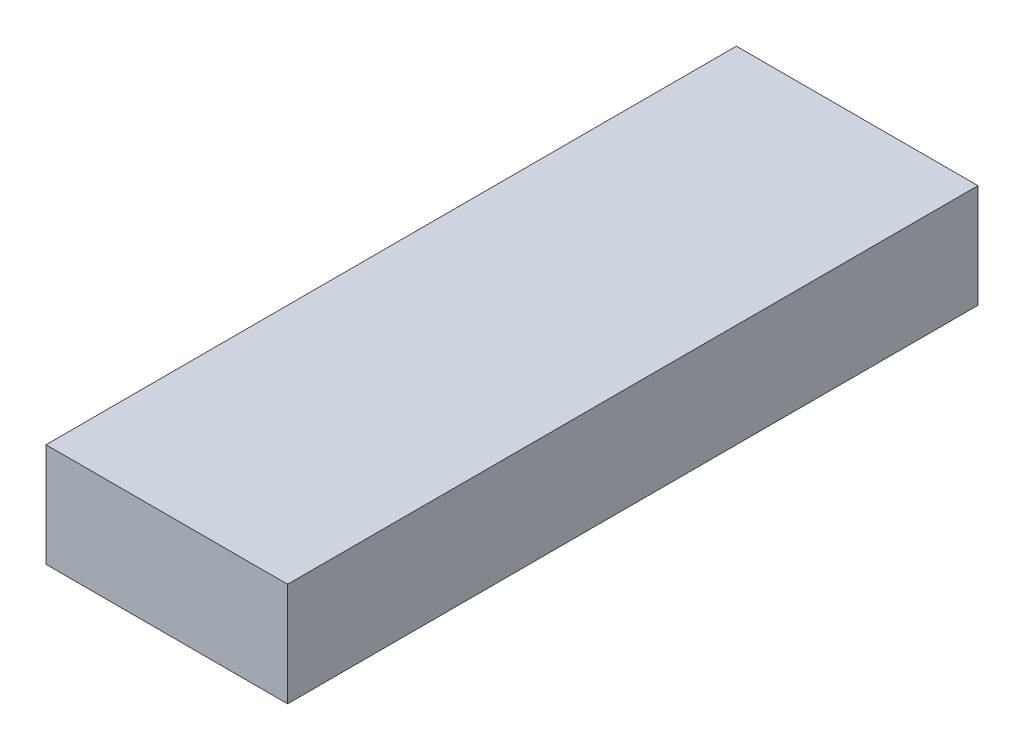
SolidWorks part; units mm, degrees
ref_plane "Front Plane" through (0, 0, 0) normal (0, 0, 1) x (1, 0, 0)
ref_plane "Top Plane" through (0, 0, 0) normal (0, 1, 0) x (1, 0, 0)
ref_plane "Right Plane" through (0, 0, 0) normal (1, 0, 0) x (0, 0, -1)
sketch "Sketch1" plane through (0, 0, 0) normal (0, 1, 0) x (1, 0, 0)
  line L1 (-350, -1000) -> (350, -1000)
  line L2 (-350, -1000) -> (-350, 1000)
  line L3 (-350, 1000) -> (350, 1000)
  line L4 (350, -1000) -> (350, 1000)
  line L5 (0, 1000) -> (0, -1000) construction
  line L6 (-350, 0) -> (350, 0) construction
  point P0 (0, 0)
  dimension "D1" = 700
  dimension "D2" = 2000
extrude "Boss-Extrude1" add sketch "Sketch1" along normal blind 300
